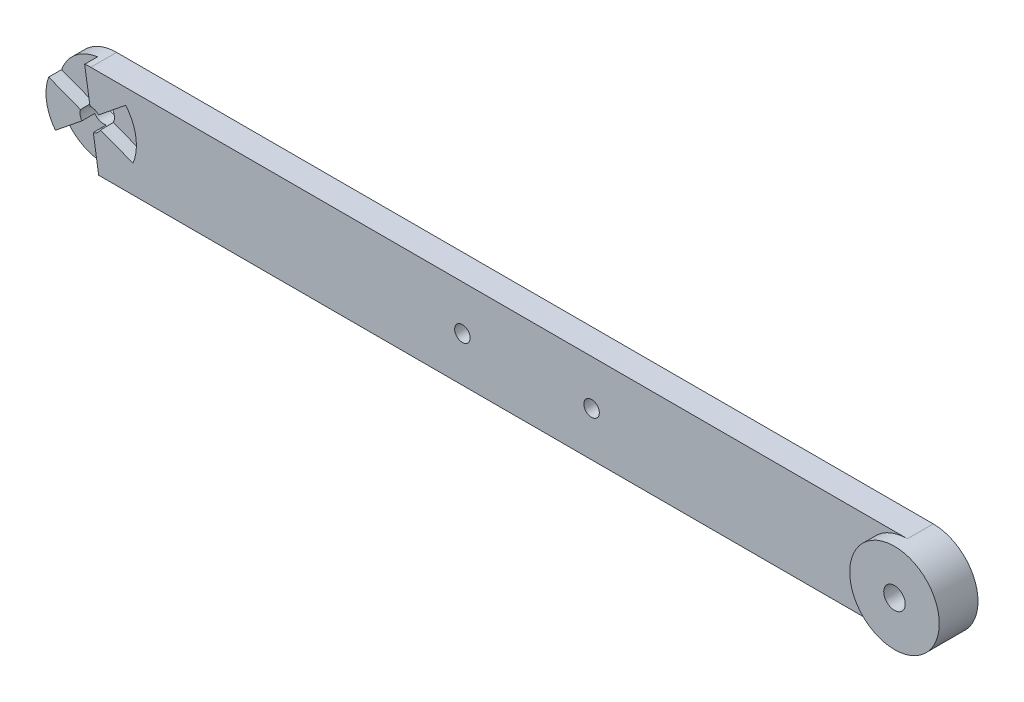
SolidWorks part; units mm, degrees
ref_plane "Front Plane" through (0, 0, 0) normal (0, 0, 1) x (1, 0, 0)
ref_plane "Top Plane" through (0, 0, 0) normal (0, 1, 0) x (1, 0, 0)
ref_plane "Right Plane" through (0, 0, 0) normal (1, 0, 0) x (0, 0, -1)
sketch "Sketch1" plane through (0, 0, 0) normal (0, 0, 1) x (1, 0, 0)
  line L0 (189.7, -10.4) -> (0, -10.4)
  line L1 (189.7, 10.4) -> (0, 10.4)
  circle A4 centre (0, 0) radius 2.5
  circle A5 centre (189.7, 0) radius 2.5
  arc A6 (0, 10.4) -> (0, -10.4) centre (0, 0) ccw
  arc A7 (189.7, -10.4) -> (189.7, 10.4) centre (189.7, 0) ccw
  arc A9 (0, -10.4) -> (0, 10.4) centre (0, 0) ccw construction
  circle A10 centre (0, 0) radius 10.4 construction
  arc A11 (189.7, 10.4) -> (189.7, -10.4) centre (189.7, 0) ccw construction
  circle A12 centre (189.7, 0) radius 10.4 construction
  circle A13 centre (189.7, 0) radius 1.4996 construction
  circle A15 centre (0, 0) radius 2.4001
  point P11 (170.2346, 97.4995)
  point P18 (75.4, 97.5)
  dimension "D1" = 5
  dimension "D3" = 1.0004
  dimension "D4" = 4.8001
  dimension "D2" = 10.4
  dimension "D5" = 189.7
extrude "Boss-Extrude1" add sketch "Sketch1" along normal blind 6 contours L0 A7 L1 A6 A4 A5
sketch "Sketch6" plane through (0, 0, 0) normal (0, 0, -1) x (-1, 0, 0)
  line L0 (0, 0) -> (6.6622, 8.2447) construction
  line L1 (0, 0) -> (-10.4, 0) construction
  line L2 (0, 0) -> (9.892, 3.8091) construction
  line L3 (0, 0) -> (1.6472, 10.4712) construction
  line L4 (2.3974, 0.7088) -> (9.9638, 3.6224)
  line L5 (0.1897, 2.4928) -> (1.4497, 10.5023)
  line L6 (-0.5848, -2.4306) -> (-1.8448, -10.4401)
  line L7 (0.0719, -0.1866) -> (9.9638, 3.6224) construction
  line L8 (-0.1976, 0.0311) -> (1.4497, 10.5023) construction
  line L9 (2.064, -1.4107) -> (8.3704, -6.5066)
  line L10 (0.1257, 0.1556) -> (8.3704, -6.5066) [skipped]
  line L11 (-0.1976, 0.0311) -> (-1.8448, -10.4401) [skipped]
  line L12 (0.0719, -0.1866) -> (-9.8201, -3.9957) [skipped]
  line L13 (0.1257, 0.1556) -> (-8.119, 6.8177) [skipped]
  line L14 (-1.8126, 1.7218) -> (-8.119, 6.8177)
  line L15 (-2.2537, -1.0821) -> (-9.8201, -3.9957)
  circle A0 centre (0, 0) radius 10.4 construction
  arc A1 (0, -10.4) -> (0, 10.4) centre (0, 0) ccw construction
  arc A2 (9.9621, 3.6217) -> (1.4494, 10.5004) centre (0, 0) ccw
  arc A3 (9.9621, 3.6217) -> (1.4494, 10.5004) centre (0, 0) ccw
  arc A4 (9.9621, 3.6217) -> (1.4494, 10.5004) centre (0, 0) ccw
  circle A5 centre (0, 0) radius 2.5 construction
  arc A6 (2.3974, 0.7088) -> (0.1897, 2.4928) centre (0, 0) ccw
  arc A7 (-0.5848, -2.4306) -> (2.064, -1.4107) centre (0, 0) ccw
  circle A8 centre (0, 0) radius 10.6 construction
  arc A9 (-1.8445, -10.4383) -> (8.369, -6.5054) centre (0, 0) ccw
  arc A10 (-1.8126, 1.7218) -> (-2.2537, -1.0821) centre (0, 0) ccw
  arc A11 (-8.1176, 6.8165) -> (-9.8183, -3.995) centre (0, 0) ccw
  point P8 (-0.7033, -1.0005)
  point P13 (7.6704, -5.9409)
  point P14 (0.0719, -0.1866)
  point P15 (9.124, 3.299)
  point P22 (10.1368, 3.0991)
  point P27 (0, 0)
  point P34 (0, 0)
  point P51 (0, 0)
  dimension "D3" = 60
  dimension "D2" = 128.94
  dimension "D4" = 30
  dimension "D6" = 0.2
  dimension "D8" = 3
  dimension "D1" = 0.2
  dimension "D5" = 0.2
  dimension "D7" = 3
extrude "Cut-Extrude3" cut sketch "Sketch6" against normal blind 3
sketch "Sketch4" plane through (0, 0, 0) normal (0, 0, -1) x (-1, 0, 0)
  arc A0 (-189.7, 10.4) -> (-189.7, -10.4) centre (-189.7, 0) ccw construction
  arc A1 (-189.7, 10.4) -> (-189.7, -10.4) centre (-189.7, 0) ccw
  arc A2 (-189.7, 10.4) -> (-189.7, -10.4) centre (-189.7, 0) cw
  circle A3 centre (-189.7, 0) radius 2.5 construction
  circle A4 centre (-189.7, 0) radius 2.5
extrude "Boss-Extrude2" add sketch "Sketch4" along normal blind 3
mirror "Mirror1" about plane through (0, 0, 0) normal (0, 0, 1) of bodies 103
sketch "Sketch7" plane through (0, 0, -6) normal (0, 0, -1) x (-1, 0, 0)
  point P0 (-116.3361, -0.0508)
  point P3 (-86.3362, 0.0015)
delete or keep bodies "Body-Delete/Keep 1" type delete bodies bodies 103
hole_wizard "M3 Clearance Hole1" positions "Sketch7" profile "Sketch8" hole size "M3" standard "ANSI Metric" end condition through all
sketch "Sketch8" plane through (116.3361, -0.0508, -6) normal (1, 0, 0) x (0, 1, 0)
  line L0 (0, 0) -> (0, 9)
  line L1 (0, 9) -> (1.8, 9)
  line L2 (1.8, 9) -> (1.8, 0)
  line L5 (1.8, 0) -> (0, 0)
  line L11 (0, -6.35) -> (0, 107.95) construction
  dimension "Thru Hole Dia." = 3.6
  dimension "Thru Hole Depth" = 9
